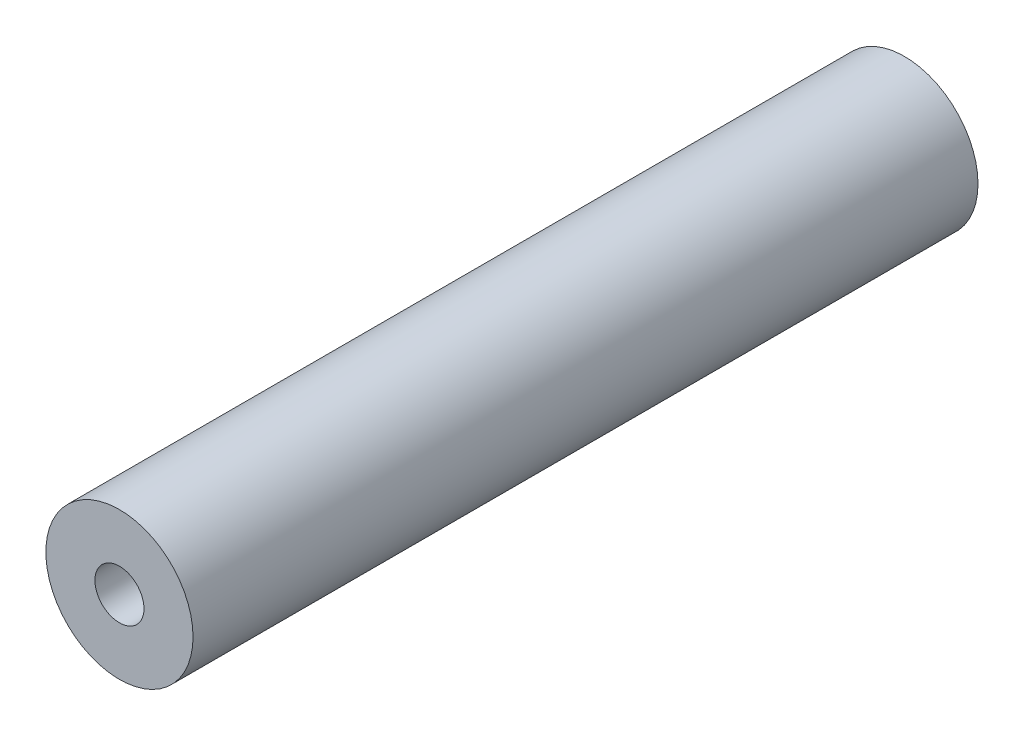
SolidWorks part; units mm, degrees
ref_plane "Front Plane" through (0, 0, 0) normal (0, 0, 1) x (1, 0, 0)
ref_plane "Top Plane" through (0, 0, 0) normal (0, 1, 0) x (1, 0, 0)
ref_plane "Right Plane" through (0, 0, 0) normal (1, 0, 0) x (0, 0, -1)
sketch "Sketch1" plane through (0, 0, 0) normal (0, 0, 1) x (1, 0, 0)
  circle A0 centre (0, 0) radius 4.7625
  circle A1 centre (0, 0) radius 1.5875
  dimension "D1" = 9.525
  dimension "D2" = 3.175
extrude "Boss-Extrude1" add sketch "Sketch1" along normal blind 50.8
